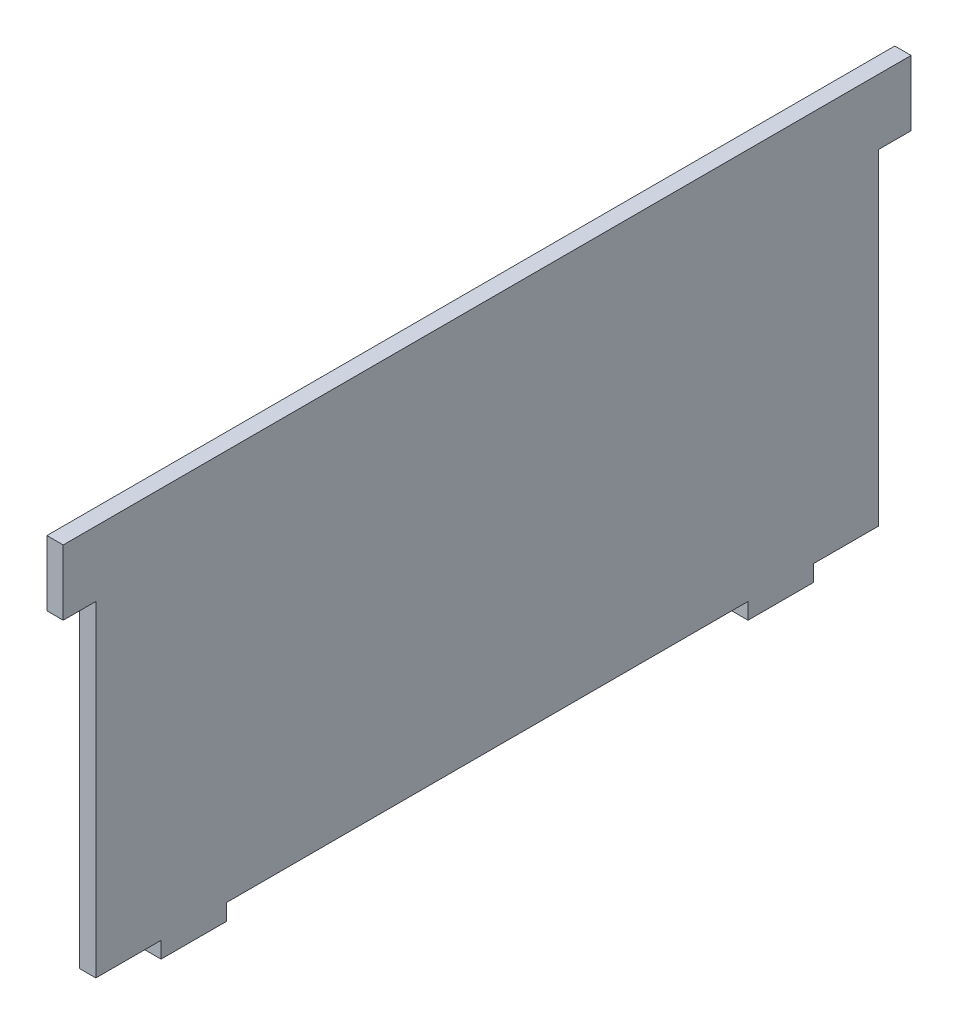
SolidWorks part; units mm, degrees
material "Perspex (TM) GS Acrylic Cast Sheet"
ref_plane "Ebene vorne" through (0, 0, 0) normal (0, 0, 1) x (1, 0, 0)
ref_plane "Ebene oben" through (0, 0, 0) normal (0, 1, 0) x (1, 0, 0)
ref_plane "Ebene rechts" through (0, 0, 0) normal (1, 0, 0) x (0, 0, -1)
sketch "Skizze2" plane through (0, 0, 0) normal (1, 0, 0) x (0, 0, -1)
  line L1 (-120, 60) -> (120, 60)
  line L2 (-120, 60) -> (-120, -60)
  line L3 (-120, -60) -> (120, -60)
  line L4 (120, 60) -> (120, -60)
  line L5 (-120, 60) -> (120, -60) construction
  line L6 (-120, -60) -> (120, 60) construction
  line L7 (-120, 60) -> (-130, 60)
  line L8 (-120, 60) -> (-120, 40)
  line L9 (-120, 40) -> (-130, 40)
  line L10 (-130, 60) -> (-130, 40)
  line L11 (-120, 60) -> (-130, 40) construction
  line L12 (-120, 40) -> (-130, 60) construction
  line L13 (120, 60) -> (130, 60)
  line L14 (120, 60) -> (120, 40)
  line L15 (120, 40) -> (130, 40)
  line L16 (130, 60) -> (130, 40)
  line L17 (120, 60) -> (130, 40) construction
  line L18 (120, 40) -> (130, 60) construction
  line L19 (100, -60) -> (80, -60)
  line L20 (100, -60) -> (100, -65)
  line L21 (100, -65) -> (80, -65)
  line L22 (80, -60) -> (80, -65)
  line L23 (-80, -60) -> (-100, -60)
  line L24 (-80, -60) -> (-80, -65)
  line L25 (-80, -65) -> (-100, -65)
  line L26 (-100, -60) -> (-100, -65)
  point P0 (0, 0)
  point P9 (-125, 50)
  point P13 (125, 50)
  dimension "D1" = 240
  dimension "D2" = 120
  dimension "D3" = 10
  dimension "D4" = 20
  dimension "D5" = 20
  dimension "D6" = 20
  dimension "D7" = 5
  dimension "D8" = 20
extrude "Aufsatz-Linear austragen1" add sketch "Skizze2" along normal blind 5
